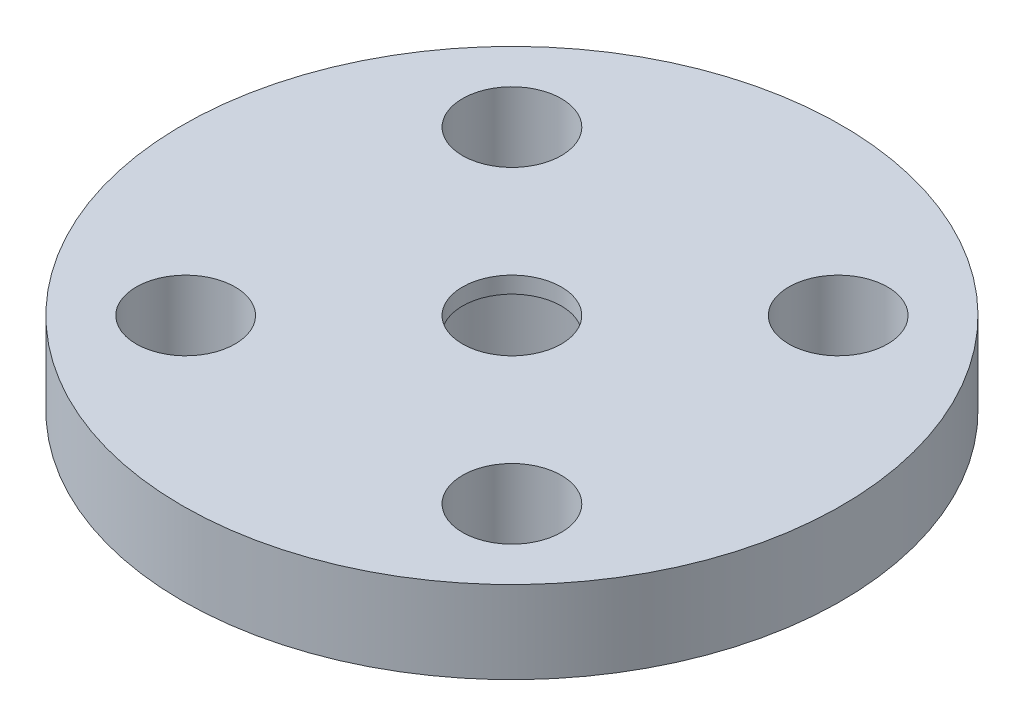
SolidWorks part; units mm, degrees
ref_plane "前视基准面" through (0, 0, 0) normal (0, 0, 1) x (1, 0, 0)
ref_plane "上视基准面" through (0, 0, 0) normal (0, 1, 0) x (1, 0, 0)
ref_plane "右视基准面" through (0, 0, 0) normal (1, 0, 0) x (0, 0, -1)
other "Configuration Table"
sketch "草图1" plane through (0, 0, 0) normal (0, 1, 0) x (1, 0, 0)
  line L1 (-4.9497, -4.9497) -> (4.9497, -4.9497) construction
  line L2 (-4.9497, -4.9497) -> (-4.9497, 4.9497) construction
  line L3 (-4.9497, 4.9497) -> (4.9497, 4.9497) construction
  line L4 (4.9497, -4.9497) -> (4.9497, 4.9497) construction
  line L5 (-4.9497, -4.9497) -> (4.9497, 4.9497) construction
  line L6 (-4.9497, 4.9497) -> (4.9497, -4.9497) construction
  circle A0 centre (0, 0) radius 10
  circle A1 centre (0, 0) radius 1.5
  circle A2 centre (-4.9497, 4.9497) radius 1.5
  circle A3 centre (4.9497, 4.9497) radius 1.5
  circle A4 centre (4.9497, -4.9497) radius 1.5
  circle A5 centre (-4.9497, -4.9497) radius 1.5
  dimension "D1" = 20
  dimension "D2" = 3
  dimension "D4" = 3
  dimension "D3" = 14
extrude "凸台-拉伸1" add sketch "草图1" along normal blind 2.5
sketch "草图2" plane through (0, 0, 0) normal (0, -1, 0) x (1, 0, 0)
  circle A0 centre (0, 0) radius 4.5
  dimension "D1" = 9
extrude "凸台-拉伸2" add sketch "草图2" along normal blind 2
sketch "草图3" plane through (0, -2, 0) normal (0, -1, 0) x (1, 0, 0)
  circle A2 centre (0, 0) radius 2.75
  dimension "D1" = 5.5
extrude "切除-拉伸1" cut sketch "草图3" against normal blind 4
